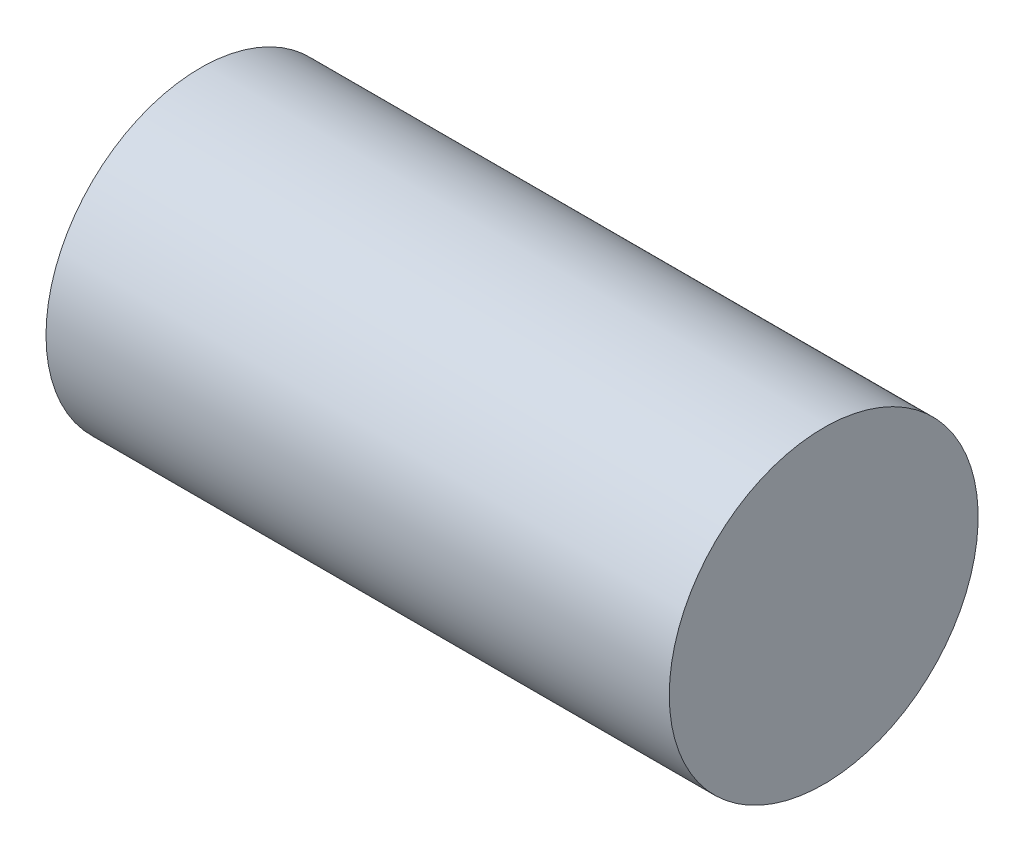
SolidWorks part; units mm, degrees
ref_plane "Płaszczyzna przednia" through (0, 0, 0) normal (0, 0, 1) x (1, 0, 0)
ref_plane "Płaszczyzna górna" through (0, 0, 0) normal (0, 1, 0) x (1, 0, 0)
ref_plane "Płaszczyzna prawa" through (0, 0, 0) normal (1, 0, 0) x (0, 0, -1)
sketch "Szkic1" plane through (0, 0, 0) normal (0, 0, 1) x (1, 0, 0)
  line L0 (0, 0) -> (149.8555, 0)
  line L1 (149.8555, 0) -> (149.8555, 37.1323)
  line L2 (149.8555, 37.1323) -> (0, 37.1323)
  line L3 (0, 37.1323) -> (0, 0)
  dimension "D1" = 149.8555
  dimension "D2" = 37.1323
revolve "Obrót1" add sketch "Szkic1" angle 360 about L0
